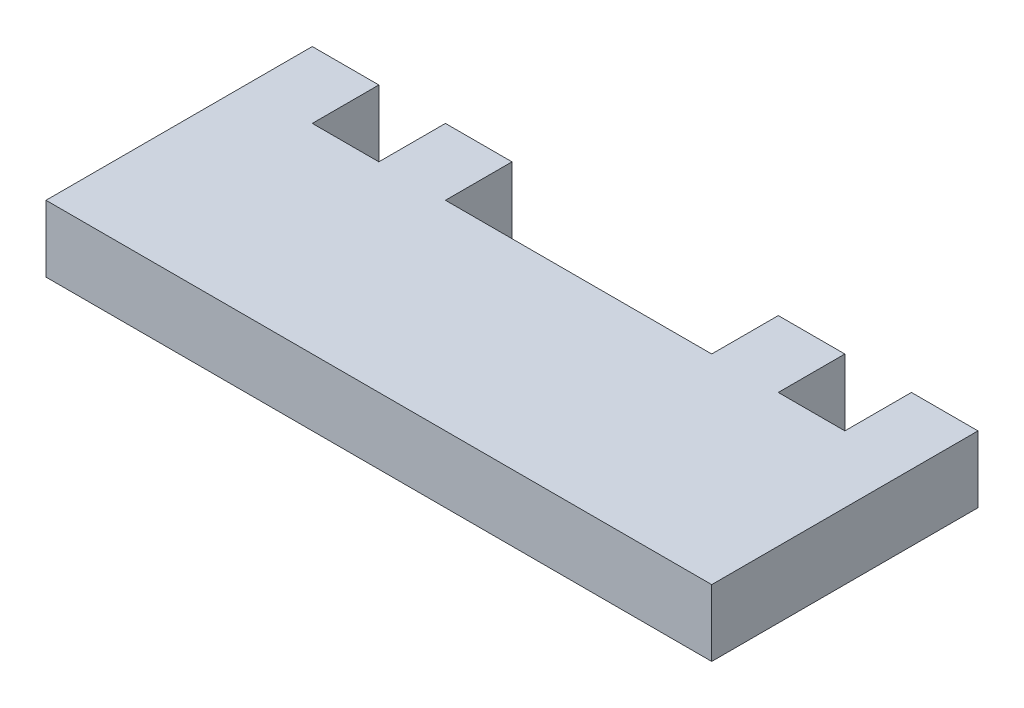
SolidWorks part; units mm, degrees
ref_plane "Front Plane" through (0, 0, 0) normal (0, 0, 1) x (1, 0, 0)
ref_plane "Top Plane" through (0, 0, 0) normal (0, 1, 0) x (1, 0, 0)
ref_plane "Right Plane" through (0, 0, 0) normal (1, 0, 0) x (0, 0, -1)
sketch "Sketch1" plane through (0, 0, 0) normal (0, 1, 0) x (1, 0, 0)
  line L0 (0, 12.7) -> (0, 9.525) construction
  line L1 (-31.75, -12.7) -> (31.75, -12.7)
  line L2 (-31.75, -12.7) -> (-31.75, 12.7)
  line L3 (-31.75, 12.7) -> (31.75, 12.7)
  line L4 (31.75, -12.7) -> (31.75, 12.7)
  line L5 (-31.75, -12.7) -> (31.75, 12.7) construction
  line L6 (-31.75, 12.7) -> (31.75, -12.7) construction
  line L7 (19.05, 12.7) -> (12.7, 12.7)
  line L8 (25.4, 6.35) -> (-25.4, 6.35)
  line L9 (25.4, 6.35) -> (25.4, 12.7)
  line L10 (25.4, 12.7) -> (-25.4, 12.7)
  line L11 (-25.4, 6.35) -> (-25.4, 12.7)
  line L12 (25.4, 6.35) -> (-25.4, 12.7) construction
  line L13 (25.4, 12.7) -> (-25.4, 6.35) construction
  line L14 (-25.4, 12.7) -> (-19.05, 12.7)
  line L15 (-25.4, 12.7) -> (-25.4, 6.35)
  line L16 (-25.4, 6.35) -> (-19.05, 6.35)
  line L17 (-19.05, 12.7) -> (-19.05, 6.35)
  line L18 (-19.05, 6.35) -> (-12.7, 6.35)
  line L19 (-19.05, 6.35) -> (-19.05, 12.7)
  line L20 (-19.05, 12.7) -> (-12.7, 12.7)
  line L21 (-12.7, 6.35) -> (-12.7, 12.7)
  line L22 (12.7, 6.35) -> (12.7, 12.7)
  line L23 (19.05, 6.35) -> (12.7, 6.35)
  line L24 (19.05, 6.35) -> (19.05, 12.7)
  point P0 (0, 0)
  dimension "D1" = 63.5
  dimension "D2" = 25.4
  dimension "D3" = 3.175
  dimension "D4" = 6.35
  dimension "D5" = 6.35
  dimension "D6" = 6.35
extrude "Boss-Extrude1" add sketch "Sketch1" along normal blind 6.35 contours L8 L11 L3 L2 L1 L4 L9 | L19 L18 L21 L20 | L7 L22 L23 L24
